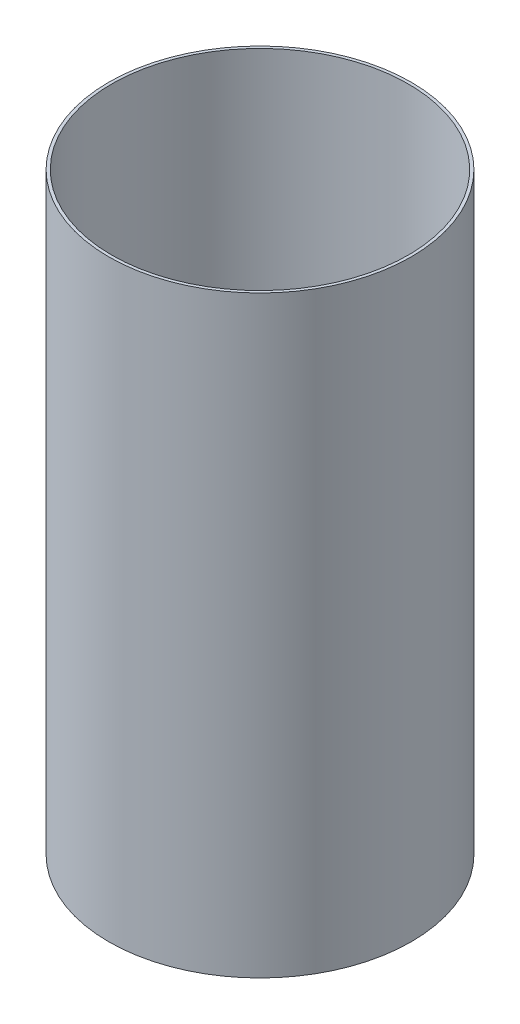
SolidWorks part; units mm, degrees
ref_plane "Спереди" through (0, 0, 0) normal (0, 0, 1) x (1, 0, 0)
ref_plane "Сверху" through (0, 0, 0) normal (0, 1, 0) x (1, 0, 0)
ref_plane "Справа" through (0, 0, 0) normal (1, 0, 0) x (0, 0, -1)
sketch "Эскиз1" plane through (0, 0, 0) normal (0, 1, 0) x (1, 0, 0)
  circle A0 centre (0, 0) radius 51
  circle A1 centre (0, 0) radius 50
  dimension "D1" = 102
  dimension "D2" = 100
extrude "Бобышка-Вытянуть1" add sketch "Эскиз1" along normal blind 200
